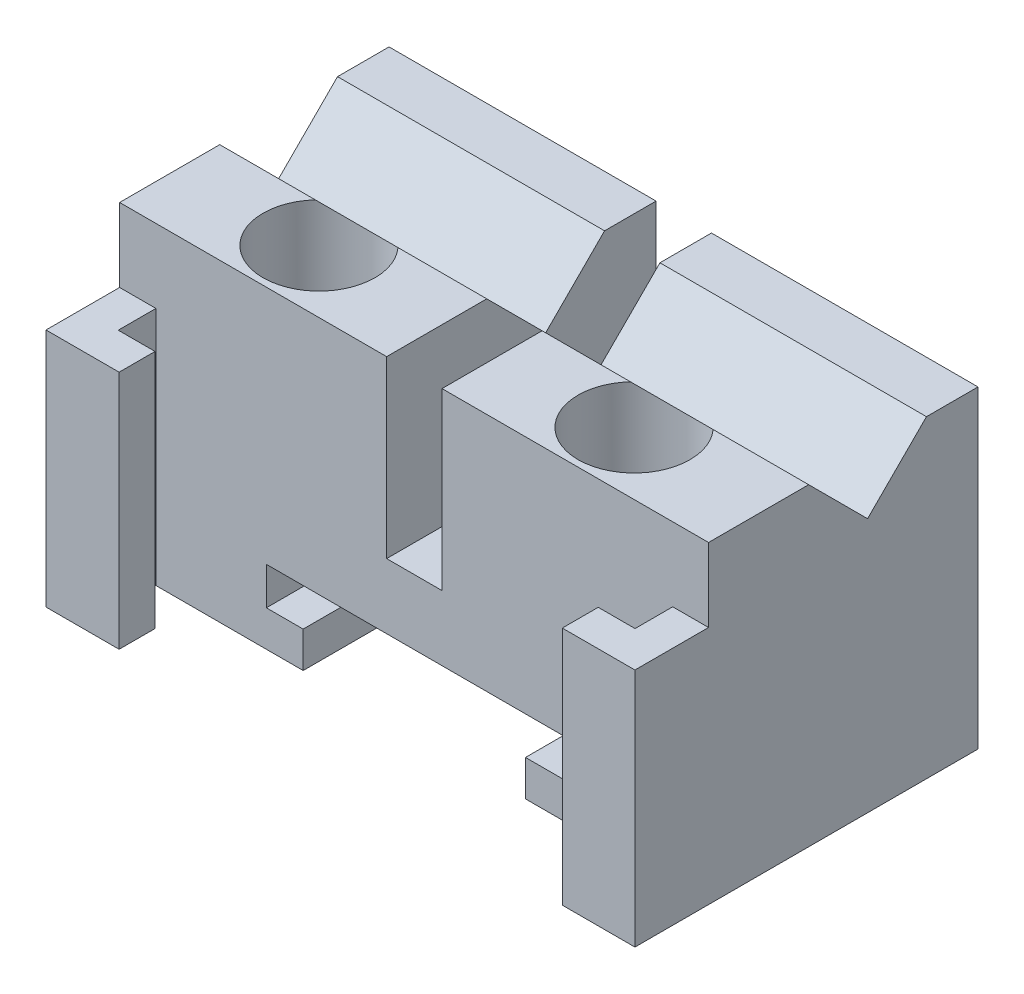
SolidWorks part; units mm, degrees
ref_plane "Alzado" through (0, 0, 0) normal (0, 0, 1) x (1, 0, 0)
ref_plane "Planta" through (0, 0, 0) normal (0, 1, 0) x (1, 0, 0)
ref_plane "Vista lateral" through (0, 0, 0) normal (1, 0, 0) x (0, 0, -1)
sketch "Croquis1" plane through (0, 0, 0) normal (0, 0, 1) x (1, 0, 0)
  line L1 (-25.4208, 13.5045) -> (25.3792, 13.5045)
  line L2 (-25.4208, 13.5045) -> (-25.4208, -13.5465)
  line L3 (-25.4208, -13.5465) -> (25.3792, -13.5465)
  line L4 (25.3792, 13.5045) -> (25.3792, -13.5465)
  line L5 (-0.0208, -13.5465) -> (-0.0208, 13.5045) construction
  line L6 (-25.4208, -0.021) -> (25.3792, -0.021) construction
  point P152 (-0.0208, -0.021)
  dimension "D1" = 27.051
  dimension "D2" = 50.8
extrude "Saliente-Extruir1" add sketch "Croquis1" along normal blind 29.591
sketch "Croquis7" plane through (0, 0, 0) normal (0, 0, -1) x (-1, 0, 0)
  line L0 (-12.7635, -7.1965) -> (12.7635, -7.1965)
  line L1 (-12.7635, -7.1965) -> (-12.7635, -10.4477)
  line L2 (-12.7635, -10.4477) -> (-9.5885, -10.4477)
  line L3 (-9.5885, -10.4477) -> (-9.5885, -13.5465)
  line L4 (-9.5885, -13.5465) -> (9.5885, -13.5465)
  line L5 (9.5885, -13.5465) -> (9.5885, -10.4477)
  line L6 (9.5885, -10.4477) -> (12.7635, -10.4477)
  line L7 (12.7635, -10.4477) -> (12.7635, -7.1965)
  point P8 (0, 0)
  point P9 (0, 0)
  dimension "D1" = 25.527
  dimension "D2" = 3.0988
  dimension "D3" = 19.177
  dimension "D4" = 3.0988
  dimension "D5" = 23.9522
  dimension "D6" = 6.35
extrude "Cortar-Extruir1" cut sketch "Croquis7" against normal through all
sketch "Croquis8" plane through (0, 0, 0) normal (0, 0, -1) x (-1, 0, 0)
  line L1 (-2.3876, 13.5045) -> (2.3876, 13.5045)
  line L2 (-2.3876, 13.5045) -> (-2.3876, -1.5831)
  line L3 (-2.3876, -1.5831) -> (2.3876, -1.5831)
  line L4 (2.3876, 13.5045) -> (2.3876, -1.5831)
  line L5 (0, -1.5831) -> (0, 13.5045) construction
  line L6 (-2.3876, 5.9607) -> (2.3876, 5.9607) construction
  point P432 (0, 5.9607)
  dimension "D1" = 15.0876
  dimension "D2" = 4.7752
  dimension "D3" = 15.0876
extrude "Cortar-Extruir2" cut sketch "Croquis8" against normal through all
sketch "Croquis9" plane through (0, 13.5045, 0) normal (0, 1, 0) x (1, 0, 0)
  line L0 (-19.1135, -29.591) -> (19.1135, -29.591)
  line L1 (-2.3876, -29.591) -> (-25.4208, -29.591) construction
  line L2 (19.1135, -29.591) -> (19.1135, -26.4922)
  line L3 (19.1135, -26.4922) -> (22.2885, -26.4922)
  line L4 (22.2885, -26.4922) -> (22.2885, -23.241)
  line L5 (22.2885, -23.241) -> (-22.2885, -23.241)
  line L6 (-22.2885, -23.241) -> (-22.2885, -26.4922)
  line L7 (-22.2885, -26.4922) -> (-19.1135, -26.4922)
  line L8 (-19.1135, -26.4922) -> (-19.1135, -29.591)
  dimension "D1" = 44.577
  dimension "D2" = 38.227
  dimension "D3" = 3.0988
  dimension "D4" = 6.35
extrude "Cortar-Extruir3" cut sketch "Croquis9" against normal through all
sketch "Croquis12" plane through (0, 13.5045, 0) normal (0, 1, 0) x (1, 0, 0)
  line L0 (25.3792, 0) -> (2.3876, 0) construction
  circle A0 centre (-13.6098, -17.8562) radius 4.826
  circle A1 centre (13.5682, -17.8562) radius 4.826
  point P9 (-24.542, -2.294)
  dimension "D1" = 17.8562
  dimension "D2" = 17.8562
  dimension "D5" = 9.652
  dimension "D6" = 9.652
  dimension "D3" = 27.178
  dimension "D4" = 11.811
extrude "Cortar-Extruir4" cut sketch "Croquis12" against normal blind 15.875 contours A0 | A1
sketch "Croquis13" plane through (25.3792, 0, 0) normal (1, 0, 0) x (0, 0, -1)
  line L1 (-29.591, 13.5045) -> (-23.241, 13.5045)
  line L2 (-29.591, 13.5045) -> (-29.591, 7.1545)
  line L3 (-29.591, 7.1545) -> (-23.241, 7.1545)
  line L4 (-23.241, 13.5045) -> (-23.241, 7.1545)
  line L5 (-26.416, 7.1545) -> (-26.416, 13.5045) construction
  line L6 (-29.591, 10.3295) -> (-23.241, 10.3295) construction
  point P112 (-26.416, 10.3295)
extrude "Cortar-Extruir5" cut sketch "Croquis13" against normal through all
sketch "Croquis14" plane through (25.3792, 0, 0) normal (1, 0, 0) x (0, 0, -1)
  line L0 (0, 13.5045) -> (0, 8.4245)
  line L1 (0, -13.5465) -> (0, 13.5045) construction
  line L2 (0, 8.4245) -> (-9.525, 8.4245)
  line L3 (-9.525, 8.4245) -> (-1.0623, 16.8873)
  line L4 (-1.0623, 16.8873) -> (-17.9877, 16.8873)
  line L5 (-17.9877, 16.8873) -> (-9.525, 8.4245)
  line M5 (0, 13.5045) -> (-23.241, 13.5045)
  dimension "D1" = 9.525
  dimension "D2" = 5.08
  dimension "D3" = 90
extrude "Cortar-Extruir6" cut sketch "Croquis14" against normal through all contours L5 L3 M5
sketch "Croquis15" plane through (0, 13.5045, 0) normal (0, 1, 0) x (1, 0, 0)
